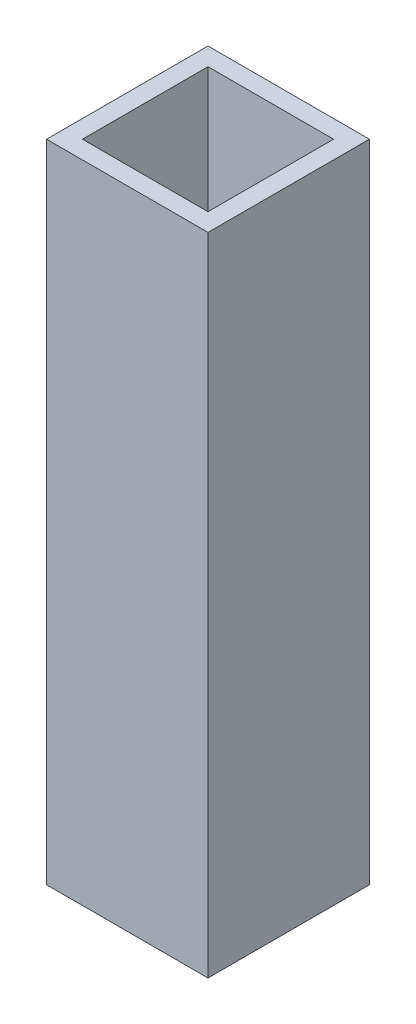
SolidWorks part; units mm, degrees
ref_plane "前视基准面" through (0, 0, 0) normal (0, 0, 1) x (1, 0, 0)
ref_plane "上视基准面" through (0, 0, 0) normal (0, 1, 0) x (1, 0, 0)
ref_plane "右视基准面" through (0, 0, 0) normal (1, 0, 0) x (0, 0, -1)
other "Configuration Table"
sketch "草图1" plane through (0, 0, 0) normal (0, 1, 0) x (1, 0, 0)
  line L1 (-1.75, 1.75) -> (1.75, 1.75)
  line L2 (-1.75, 1.75) -> (-1.75, -1.75)
  line L3 (-1.75, -1.75) -> (1.75, -1.75)
  line L4 (1.75, 1.75) -> (1.75, -1.75)
  line L5 (-1.75, 1.75) -> (1.75, -1.75) construction
  line L6 (-1.75, -1.75) -> (1.75, 1.75) construction
  line L7 (-2.25, 2.25) -> (2.25, 2.25)
  line L8 (-2.25, 2.25) -> (-2.25, -2.25)
  line L9 (-2.25, -2.25) -> (2.25, -2.25)
  line L10 (2.25, 2.25) -> (2.25, -2.25)
  line L11 (-2.25, 2.25) -> (2.25, -2.25) construction
  line L12 (-2.25, -2.25) -> (2.25, 2.25) construction
  point P0 (0, 0)
  point P6 (0, 0)
  dimension "D1" = 4.5
  dimension "D2" = 4.5
  dimension "D3" = 3.5
  dimension "D4" = 3.5
extrude "凸台-拉伸1" add sketch "草图1" along normal blind 18
